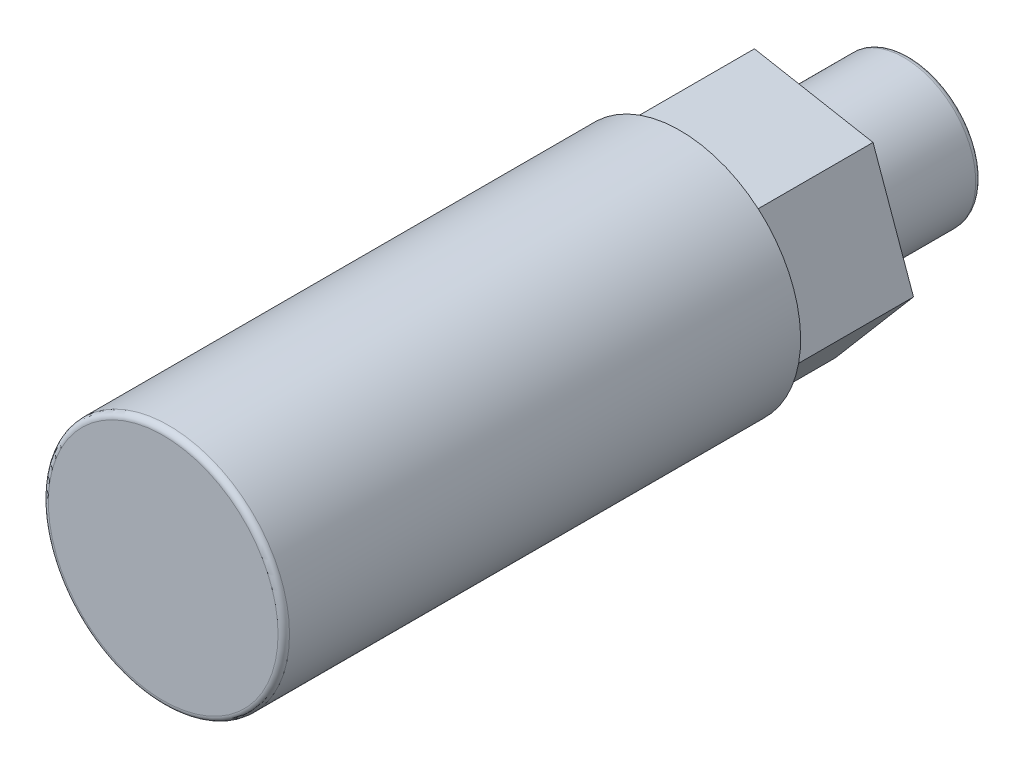
SolidWorks part; units mm, degrees
ref_plane "前视基准面" through (0, 0, 0) normal (0, 0, 1) x (1, 0, 0)
ref_plane "上视基准面" through (0, 0, 0) normal (0, 1, 0) x (1, 0, 0)
ref_plane "右视基准面" through (0, 0, 0) normal (1, 0, 0) x (0, 0, -1)
sketch "草图1" plane through (0, 0, 0) normal (0, 0, 1) x (1, 0, 0)
  circle A0 centre (0, 0) radius 10.5
  dimension "D1" = 21
extrude "凸台-拉伸1" add sketch "草图1" along normal blind 45
sketch "草图2" plane through (0, 0, 0) normal (0, 0, -1) x (-1, 0, 0)
  line L1 (6.8052, -7.9962) -> (10.3275, 1.8954)
  line L2 (10.3275, 1.8954) -> (3.5223, 9.8916)
  line L3 (3.5223, 9.8916) -> (-6.8052, 7.9962)
  line L4 (-6.8052, 7.9962) -> (-10.3275, -1.8954)
  line L5 (-10.3275, -1.8954) -> (-3.5223, -9.8916)
  line L6 (-3.5223, -9.8916) -> (6.8052, -7.9962)
  circle A0 centre (0, 0) radius 9.0933 construction
extrude "凸台-拉伸2" add sketch "草图2" along normal blind 10
sketch "草图3" plane through (0, 0, -10) normal (0, 0, -1) x (-1, 0, 0)
  circle A0 centre (0, 0) radius 6.25
  dimension "D1" = 12.5
extrude "凸台-拉伸3" add sketch "草图3" along normal blind 10
fillet "圆角1" radius 0.5 2 edges at (10.5, 0, 45) (-6.25, 0, -20)
sketch "草图4" plane through (0, 0, -20) normal (0, 0, -1) x (-1, 0, 0)
  circle A0 centre (0, 0) radius 3.9051
extrude "切除-拉伸1" cut sketch "草图4" against normal blind 60
